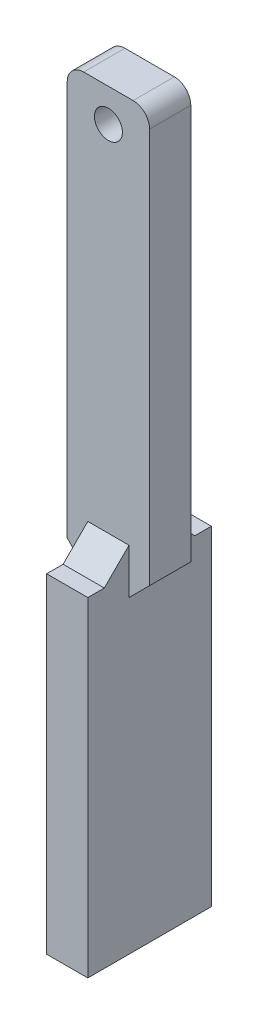
SolidWorks part; units mm, degrees
ref_plane "Ön Düzlem" through (0, 0, 0) normal (0, 0, 1) x (1, 0, 0)
ref_plane "Üst Düzlem" through (0, 0, 0) normal (0, 1, 0) x (1, 0, 0)
ref_plane "Sağ Düzlem" through (0, 0, 0) normal (1, 0, 0) x (0, 0, -1)
sketch "Çizim1" plane through (0, 0, 0) normal (0, 0, 1) x (1, 0, 0)
  line L0 (0, 0) -> (10, 0)
  line L1 (10, 0) -> (10, -50)
  line L3 (0, -50) -> (0, 0)
  line L4 (10, -50) -> (5.0503, -54.9497)
  line L5 (5.0503, -54.9497) -> (0, -50)
  dimension "D1" = 10
  dimension "D2" = 50
extrude "Yükseklik-Ekstrüzyon1" add sketch "Çizim1" along normal blind 5
fillet "Radyus1" radius 2 2 edges at (0, 0, 2.5) (10, 0, 2.5)
sketch "Çizim2" plane through (0, 0, 5) normal (0, 0, 1) x (1, 0, 0)
  line L0 (8, 0) -> (2, 0) construction
  circle A0 centre (5, -4) radius 1.7
  dimension "D1" = 4
extrude "Kes-Ekstrüzyon1" cut sketch "Çizim2" against normal blind 12
sketch "Çizim3" plane through (0, -50, 0) normal (0, -1, 0) x (1, 0, 0)
  line L0 (7.5, 10) -> (2.5, 10)
  line L1 (2.5, 10) -> (2.5, -5)
  line L2 (7.5, 10) -> (7.5, -5)
  line L3 (7.5, -5) -> (3.3, -5)
  line L4 (2.5, -5) -> (3.3, -5)
  line L6 (10, 5) -> (10, 0) construction
  dimension "D1" = 2.5
extrude "Yükseklik-Ekstrüzyon2" add sketch "Çizim3" along normal blind 40
chamfer "Pah1" distance 3 angle 45 2 edges at (5, -50, 0) (5, -50, 5)
